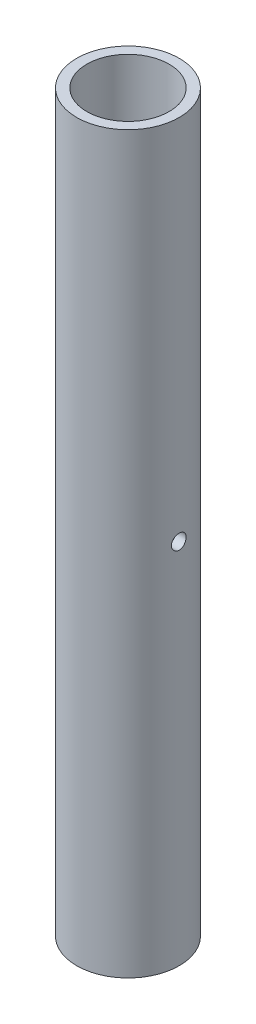
SolidWorks part; units mm, degrees
material "PVC Rigid"
ref_plane "Front Plane" through (0, 0, 0) normal (0, 0, 1) x (1, 0, 0)
ref_plane "Top Plane" through (0, 0, 0) normal (0, 1, 0) x (1, 0, 0)
ref_plane "Right Plane" through (0, 0, 0) normal (1, 0, 0) x (0, 0, -1)
sketch "Sketch2" plane through (0, 0, 0) normal (0, 1, 0) x (1, 0, 0)
  circle A0 centre (0, 0) radius 17.45
  circle A1 centre (0, 0) radius 14
  dimension "D1" = 28
  dimension "D2" = 34.9
extrude "Boss-Extrude1" add sketch "Sketch2" against normal blind 250
ref_plane "Plane1" through (17.45, 0, 0) normal (1, 0, 0) x (0, 0, -1)
hole_wizard "Tap Drill for M6x1.0 Tap1" positions "Sketch3" profile "Sketch4" hole size "M6x1.0" standard "ANSI Metric" end condition through all
sketch "Sketch3" plane through (17.45, 0, 0) normal (1, 0, 0) x (0, 0, -1)
  line L0 (14, 0) -> (-14, 0) construction
  line L1 (-17.45, 0) -> (-17.45, -250) construction
  point P0 (0, -125)
  dimension "D1" = 125
  dimension "D2" = 17.45
sketch "Sketch4" plane through (17.45, -125, 0) normal (0, 1, 0) x (0, 0, -1)
  line L0 (0, 0) -> (0, 34.9)
  line L1 (0, 34.9) -> (2.5, 34.9)
  line L2 (2.5, 34.9) -> (2.5, 0)
  line L5 (2.5, 0) -> (0, 0)
  line L11 (0, -6.35) -> (0, 107.95) construction
  dimension "Thru Hole Dia." = 5
  dimension "Thru Hole Depth" = 34.9
